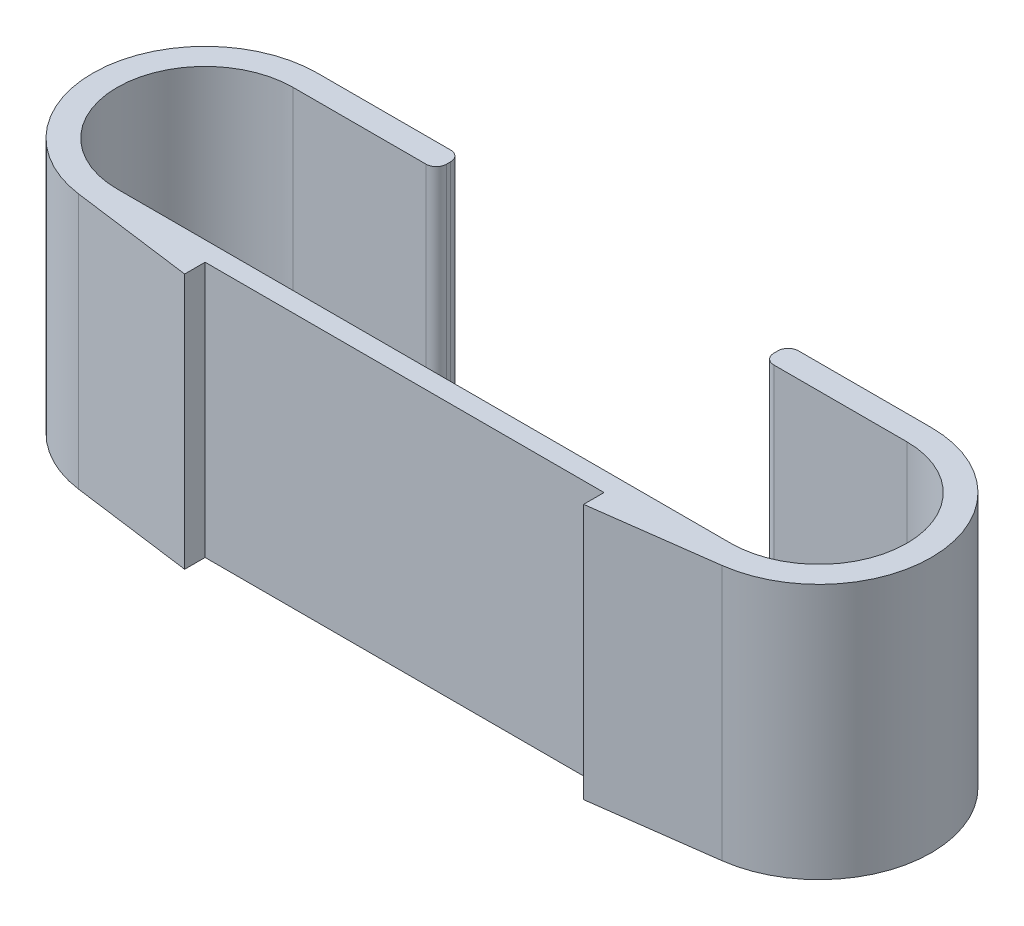
SolidWorks part; units mm, degrees
material "ABS"
ref_plane "Front Plane" through (0, 0, 0) normal (0, 0, 1) x (1, 0, 0)
ref_plane "Top Plane" through (0, 0, 0) normal (0, 1, 0) x (1, 0, 0)
ref_plane "Right Plane" through (0, 0, 0) normal (1, 0, 0) x (0, 0, -1)
sketch "Sketch1" plane through (0, 0, 0) normal (0, 1, 0) x (1, 0, 0)
  line L0 (0, 0) -> (-30, 0)
  line L1 (-30, 22) -> (-16, 22)
  arc A0 (-30, 0) -> (-30, 22) centre (-30, 11) cw
  dimension "D1" = 11
  dimension "D2" = 14
  dimension "D3" = 30
extrude "Extrude-Thin1" add sketch "Sketch1" along normal blind 25 thin
sketch "Sketch2" plane through (0, 0, 0) normal (0, 1, 0) x (1, 0, 0)
  line L0 (-30, 22) -> (-30, 0)
  arc A0 (-30, 0) -> (-30, 22) centre (-30, 11) cw
  point P4 (-30, 0)
extrude "Boss-Extrude1" add sketch "Sketch2" along normal blind 1.2
sketch "Sketch4" plane through (0, 0, 0) normal (0, 1, 0) x (1, 0, 0)
  line L0 (0, 0) -> (-30, 0) construction
  line L1 (-19.5, 0) -> (-19.5, -1.5)
  line L2 (-19.5, -1.5) -> (-31.4562, 0.0968)
  line L3 (-31.4562, 0.0968) -> (-19.5, 0)
  arc A0 (-30, 22) -> (-30, 0) centre (-30, 11) ccw construction
  point P8 (0, 0)
  dimension "D1" = 19.5
  dimension "D2" = 1.5
extrude "Boss-Extrude2" add sketch "Sketch4" along normal up to surface (25 mm away) up to face at (-21.45, 25, -11)
mirror "Mirror1" about plane through (0, 25, -2.4) normal (1, 0, 0) of "Boss-Extrude1", "Extrude-Thin1", "Boss-Extrude2"
fillet "Fillet1" radius 1 4 edges at (-16, 12.5, -22) (-16, 12.5, -19.6) (16, 12.5, -22) (16, 12.5, -19.6)
fillet "Fillet2" radius 5 4 edges at (-30, 0.6, -19.6) (-30, 0.6, -2.4) (30, 0.6, -19.6) (30, 0.6, -2.4)
sketch "Sketch6" plane through (0, 0, 0) normal (0, 0, 1) x (1, 0, 0)
  line L1 (-19.5, 0) -> (19.5, 0)
  line L2 (-19.5, 0) -> (-19.5, 25)
  line L3 (-19.5, 25) -> (19.5, 25)
  line L4 (19.5, 0) -> (19.5, 25)
extrude "Cut-Extrude1" cut sketch "Sketch6" against normal blind 0.5
